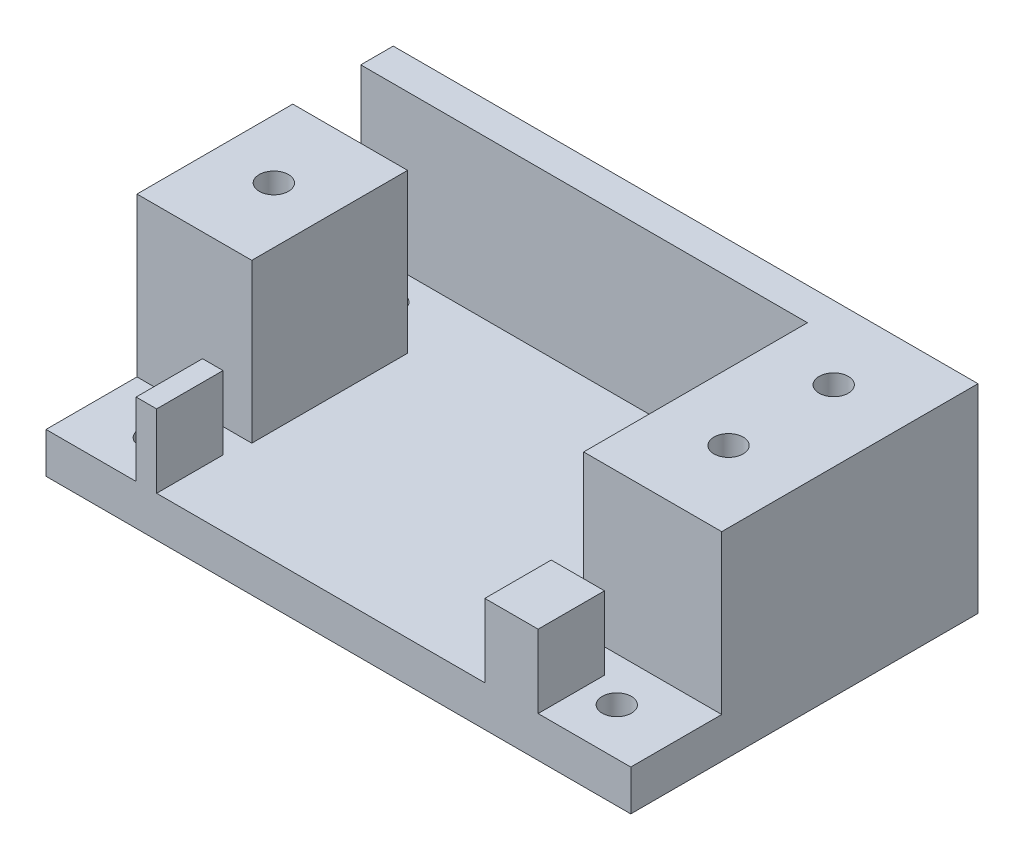
SolidWorks part; units mm, degrees
ref_plane "Front" through (0, 0, 0) normal (0, 0, 1) x (1, 0, 0)
ref_plane "Top" through (0, 0, 0) normal (0, 1, 0) x (1, 0, 0)
ref_plane "Right" through (0, 0, 0) normal (1, 0, 0) x (0, 0, -1)
sketch "Sketch2" plane through (0, 0, 0) normal (0, 1, 0) x (1, 0, 0)
  line L1 (0, 0) -> (72, 0)
  line L2 (0, 0) -> (0, 40)
  line L3 (0, 40) -> (72, 40)
  line L4 (72, 0) -> (72, 40)
  dimension "D1" = 40
  dimension "D2" = 72
extrude "Boss-Extrude1" add sketch "Sketch2" along normal blind 5
sketch "Sketch3" plane through (0, 5, 0) normal (0, 1, 0) x (1, 0, 0)
  line L0 (0, 40) -> (0, 0) construction
  line L1 (14.1359, 11.2) -> (0, 11.2)
  line L2 (14.1359, 11.2) -> (14.1359, 30.3869)
  line L3 (14.1359, 30.3869) -> (0, 30.3869)
  line L4 (0, 11.2) -> (0, 30.3869)
  line L5 (59.6159, 11.2) -> (8.3159, 11.2) construction
  line L6 (55, 11.2) -> (72, 11.2)
  line L7 (55, 11.2) -> (55, 40)
  line L8 (55, 40) -> (72, 40)
  line L9 (72, 11.2) -> (72, 40)
  line L10 (72, 0) -> (72, 40) construction
  line L11 (72, 40) -> (0, 40) construction
  line L13 (0, 42.755) -> (72, 42.755)
  line L14 (0, 42.755) -> (0, 38.755)
  line L15 (0, 38.755) -> (72, 38.755)
  line L16 (72, 42.755) -> (72, 38.755)
  line M3 (0, 40) -> (0, 0)
  line M5 (72, 0) -> (72, 40)
  dimension "D1" = 17
  dimension "D2" = 0
  dimension "D3" = 4
extrude "Boss-Extrude2" add sketch "Sketch3" along normal blind 19.5 and the other way blind 5 contours L2 L3 L1 M3 | L15 L7 L6 M5
sketch "Sketch4" plane through (0, 5, 0) normal (0, 1, 0) x (1, 0, 0)
  line L0 (0, 38.755) -> (0, 30.3869) construction
  line L1 (0, 11.2) -> (0, 0) construction
  line L2 (72, 0) -> (72, 11.2) construction
  circle A0 centre (7.5, 34.6485) radius 1.8
  circle A1 centre (7.5, 5.7783) radius 1.8
  circle A2 centre (64.5, 5.7783) radius 1.8
  point P12 (72, 5.6)
  dimension "D1" = 7.5
  dimension "D3" = 7.5
  dimension "D2" = 7.5
extrude "Cut-Extrude1" cut sketch "Sketch4" against normal blind 30 from surface at 19.5 starting at face at (7.0679, 24.5, -20.7934)
sketch "Sketch5" plane through (0, 5, 0) normal (0, 1, 0) x (1, 0, 0)
  line L0 (0, 0) -> (72, 0) construction
  line L1 (54.1817, 5.1925) -> (60.5719, 5.1925)
  line L2 (54.1817, 5.1925) -> (54.1817, 0)
  line L3 (54.1817, 0) -> (60.5719, 0)
  line L4 (60.5719, 5.1925) -> (60.5719, 0)
  line L5 (54.1817, 5.1925) -> (60.5719, 6.714)
  line L6 (60.5719, 5.1925) -> (60.5719, 6.714)
sketch "Sketch7" plane through (0, 5, 0) normal (0, 1, 0) x (1, 0, 0)
  line L7 (0, 0) -> (72, 0) construction
  line L8 (13.3167, 5.4711) -> (11.0828, 5.4711)
  line L9 (13.3167, 5.4711) -> (13.3167, 0)
  line L10 (13.3167, 0) -> (11.0828, 0)
  line L11 (11.0828, 5.4711) -> (11.0828, 0)
  line L12 (13.3167, 5.4711) -> (11.0828, 6.0742)
  line L13 (11.0828, 6.0742) -> (11.0828, 5.4711)
  line L14 (11.0828, 5.4711) -> (13.3167, 5.4711)
sketch "Sketch8" plane through (0, 5, 0) normal (0, 1, 0) x (1, 0, 0)
  line L0 (0, 0) -> (72, 0) construction
  line L1 (11.0932, 8.1772) -> (13.6205, 8.1772)
  line L2 (11.0932, 8.1772) -> (11.0932, 0)
  line L3 (11.0932, 0) -> (13.6205, 0)
  line L4 (13.6205, 8.1772) -> (13.6205, 0)
  line L6 (54.0304, 8.1772) -> (60.594, 8.1772)
  line L7 (54.0304, 8.1772) -> (54.0304, 0)
  line L8 (54.0304, 0) -> (60.594, 0)
  line L9 (60.594, 8.1772) -> (60.594, 0)
extrude "Boss-Extrude7" add sketch "Sketch8" along normal blind 9
sketch "Sketch9" plane through (0, 24.5, 0) normal (0, 1, 0) x (1, 0, 0)
  circle A0 centre (7.2441, 20.8097) radius 1.8
  circle A1 centre (63.2344, 20.8097) radius 1.8
  circle A2 centre (63.2344, 33.755) radius 1.8
extrude "Cut-Extrude2" cut sketch "Sketch9" against normal blind 53
